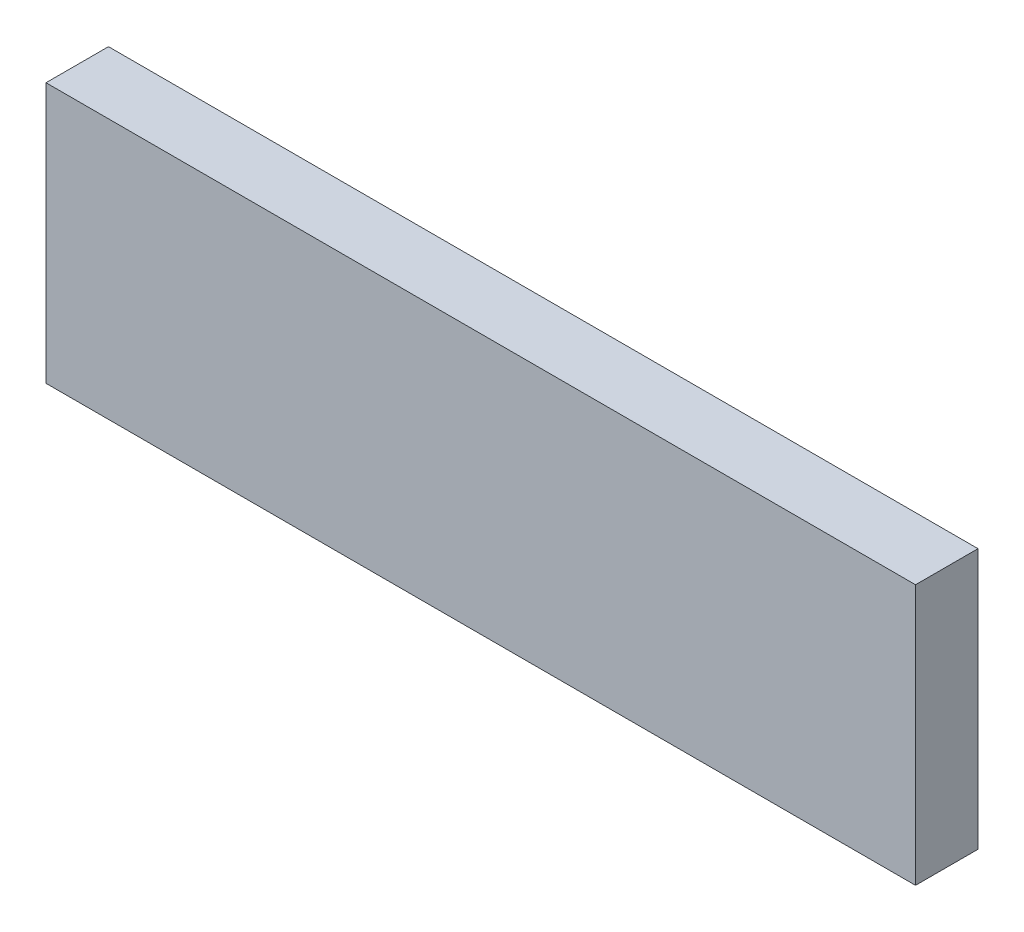
SolidWorks part; units mm, degrees
ref_plane "Plano frontal" through (0, 0, 0) normal (0, 0, 1) x (1, 0, 0)
ref_plane "Plano superior" through (0, 0, 0) normal (0, 1, 0) x (1, 0, 0)
ref_plane "Plano direito" through (0, 0, 0) normal (1, 0, 0) x (0, 0, -1)
sketch "Esboço1" plane through (0, 0, 0) normal (0, 0, 1) x (1, 0, 0)
  line L1 (-83.5, 25) -> (83.5, 25)
  line L2 (-83.5, 25) -> (-83.5, -25)
  line L3 (-83.5, -25) -> (83.5, -25)
  line L4 (83.5, 25) -> (83.5, -25)
  line L5 (-83.5, 25) -> (83.5, -25) construction
  line L6 (-83.5, -25) -> (83.5, 25) construction
  point P0 (0, 0)
extrude "Ressalto-extrusão1" add sketch "Esboço1" along normal mid plane 12
ref_plane "Plano1" through (0, -25, 0) normal (0, -1, 0) x (-1, 0, 0)
sketch "Esboço3" plane through (0, -25, 0) normal (0, -1, 0) x (-1, 0, 0)
  circle A0 centre (77.5, 0) radius 1.5
  circle A1 centre (-77.5, 0) radius 1.5
  dimension "D1" = 3
  dimension "D2" = 3
extrude "Corte-extrusão1" cut sketch "Esboço3" against normal mid plane 30
